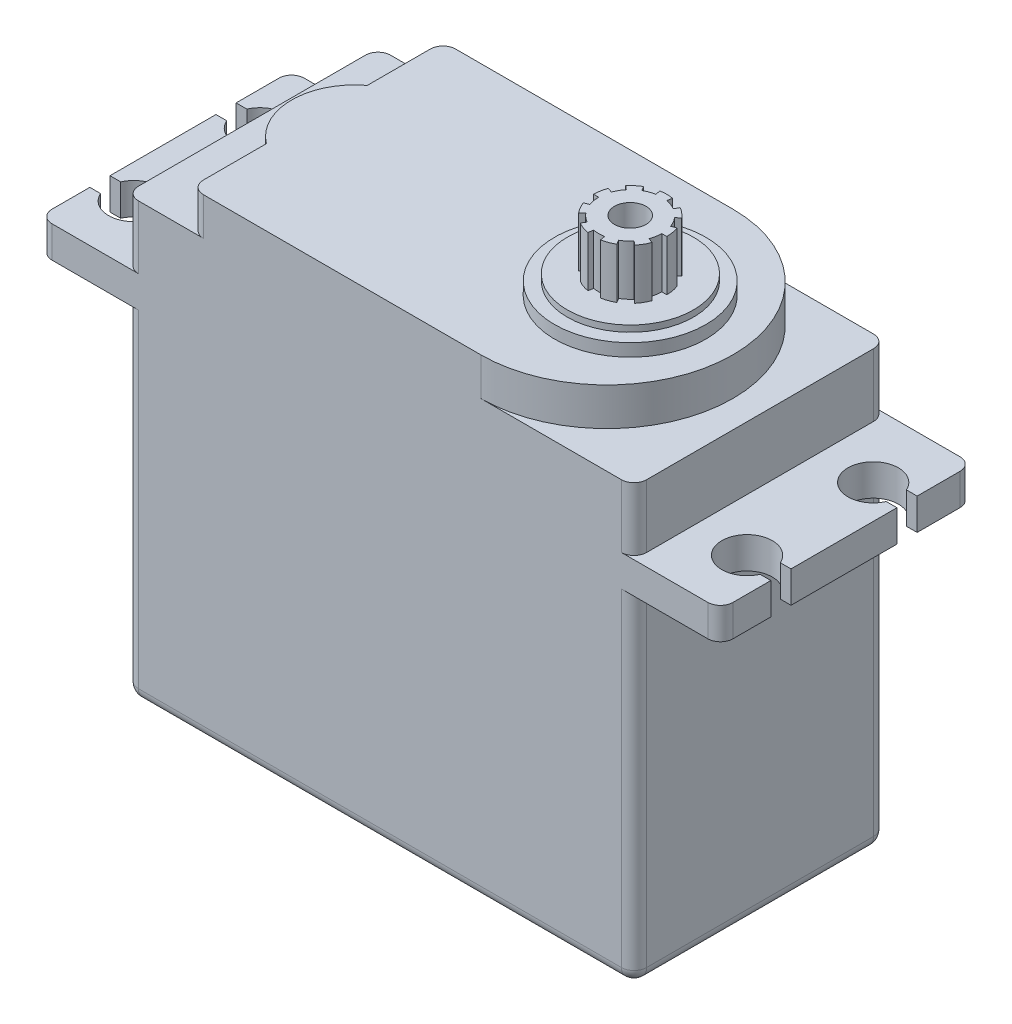
SolidWorks part; units mm, degrees
ref_plane "前视基准面" through (0, 0, 0) normal (0, 0, 1) x (1, 0, 0)
ref_plane "上视基准面" through (0, 0, 0) normal (0, 1, 0) x (1, 0, 0)
ref_plane "右视基准面" through (0, 0, 0) normal (1, 0, 0) x (0, 0, -1)
sketch "草图1" plane through (0, 0, 0) normal (0, 0, 1) x (1, 0, 0)
  line L0 (0, 0) -> (-50000, 0) construction
  line L1 (0, 0) -> (0, 50000) construction
  line L2 (20.15, 8) -> (27, 8)
  line L3 (-20.15, 18.5) -> (20.15, 18.5)
  line L4 (-20.15, 18.5) -> (-20.15, 10.5)
  line L5 (-20.15, -19) -> (20.15, -19)
  line L6 (20.15, 18.5) -> (20.15, 10.5)
  line L7 (-27, 10.5) -> (-20.15, 10.5)
  line L8 (-27, 10.5) -> (-27, 8)
  line L9 (-27, 8) -> (-20.15, 8)
  line L10 (27, 10.5) -> (27, 8)
  line L11 (20.15, 10.5) -> (27, 10.5)
  line L12 (20.15, 8) -> (20.15, -19)
  line L13 (-20.15, 8) -> (-20.15, -19)
  dimension "D1" = 8
  dimension "D2" = 6.85
  dimension "D3" = 2.5
  dimension "D4" = 40.3
  dimension "D5" = 27
  dimension "D6" = 54
  dimension "D7" = 20.15
extrude "凸台-拉伸1" add sketch "草图1" along normal blind 20
fillet "圆角1" radius 1 18 edges at (-20.15, 14.5, 20) (20.15, 14.5, 20) (20.15, 18.5, 10) (-20.15, 18.5, 10) (20.15, 14.5, 0) (-20.15, 14.5, 0) (-20.15, -19, 10) (0, -19, 20) (20.15, -19, 10) (0, -19, 0) (-20.15, -5.5, 0) (20.15, -5.5, 0) (20.15, -5.5, 20) (-20.15, -5.5, 20) (27, 9.25, 0) (27, 9.25, 20) (-27, 9.25, 0) (-27, 9.25, 20)
sketch "草图2" plane through (0, 10.5, 0) normal (0, 1, 0) x (1, 0, 0)
  line L0 (-0.1717, -10.2) -> (49999.8283, -10.2) construction
  line L1 (0, 0) -> (0, -50000) construction
  line L2 (-26.148, -4.4) -> (-29.2227, -4.4)
  line L3 (-24.315, -5.2) -> (-30.8838, -5.2) construction
  line L4 (-24, -15) -> (-30.5688, -15) construction
  line L5 (-29.2227, -4.4) -> (-29.2227, -6)
  line L6 (-26.148, -6) -> (-29.2227, -6)
  line L7 (-26.148, -14.4) -> (-29.2227, -14.4)
  line L8 (-29.2227, -16) -> (-29.2227, -14.4)
  line L9 (-26.148, -16) -> (-29.2227, -16)
  line L10 (26.148, -16) -> (29.2227, -16)
  line L11 (29.2227, -16) -> (29.2227, -14.4)
  line L12 (26.148, -14.4) -> (29.2227, -14.4)
  line L13 (29.2227, -4.4) -> (29.2227, -6)
  line L14 (26.148, -6) -> (29.2227, -6)
  line L15 (26.148, -4.4) -> (29.2227, -4.4)
  arc A0 (-26.148, -14.4) -> (-26.148, -16) centre (-24.315, -15.2) cw
  arc A1 (26.148, -14.4) -> (26.148, -16) centre (24.315, -15.2) ccw
  arc A2 (-26.148, -6) -> (-26.148, -4.4) centre (-24.315, -5.2) ccw
  arc A3 (26.148, -6) -> (26.148, -4.4) centre (24.315, -5.2) cw
  point P21 (-29.2227, -5.2)
  dimension "D2" = 10
  dimension "D1" = 48.63
  dimension "D3" = 2
extrude "切除-拉伸1" cut sketch "草图2" against normal blind 20
sketch "草图3" plane through (0, 18.5, 0) normal (0, 1, 0) x (1, 0, 0)
  line L0 (-40.2617, -10) -> (49959.7383, -10) construction
  line L1 (-14, 0) -> (8, 0)
  line L2 (-15, -1) -> (-15, -6)
  line L3 (-14, -20) -> (8, -20)
  line L4 (-15, -14) -> (-15, -19)
  line L5 (0, 0) -> (0, 50000) construction
  line L7 (-26.8677, 6.7729) -> (25, 6.7729)
  line L8 (-26.8677, 6.7729) -> (-26.8677, -28.4888)
  line L9 (-26.8677, -28.4888) -> (25, -28.4888)
  line L10 (25, 6.7729) -> (25, -28.4888)
  arc A0 (8, -20) -> (8, 0) centre (8, -10) ccw
  arc A1 (-15, -6) -> (-15, -14) centre (-12, -10) ccw
  arc A2 (-14, -20) -> (-15, -19) centre (-14, -19) cw
  arc A3 (-15, -1) -> (-14, 0) centre (-14, -1) cw
  dimension "D2" = 1
  dimension "D1" = 25
extrude "切除-拉伸2" cut sketch "草图3" against normal blind 3
sketch "草图4" plane through (0, 18.5, 0) normal (0, 1, 0) x (1, 0, 0)
  line L0 (27, -14.4) -> (27, -6) construction
  circle A0 centre (9.85, -10) radius 6
  dimension "D1" = 17.15
extrude "凸台-拉伸2" add sketch "草图4" along normal blind 1
sketch "草图5" plane through (0, 19.5, 0) normal (0, 1, 0) x (1, 0, 0)
  line L0 (27, -14.4) -> (27, -6) construction
  circle A0 centre (9.8513, -9.9876) radius 5
  point P2 (27, -10.2)
  dimension "D1" = 17.15
extrude "凸台-拉伸3" add sketch "草图5" along normal blind 0.5
sketch "草图6" plane through (0, 20, 0) normal (0, 1, 0) x (1, 0, 0)
  line L1 (10.2841, -7.538) -> (10.3536, -7.1441)
  line L3 (11.3, -7.4885) -> (11.1, -7.8349)
  line L5 (12.0715, -8.1359) -> (11.7651, -8.393)
  line L7 (12.5751, -9.0081) -> (12.1992, -9.1449)
  line L8 (6.95, -10) -> (7.35, -10)
  line L10 (7.5008, -9.1449) -> (7.1249, -9.0081)
  line L13 (8.6, -7.8349) -> (8.4, -7.4885)
  line L14 (7.9349, -8.393) -> (7.6285, -8.1359)
  line L15 (9.4159, -7.538) -> (9.3464, -7.1441)
  line L16 (9.4159, -12.462) -> (9.3464, -12.8559)
  line L19 (8.4, -12.5115) -> (8.6, -12.1651)
  line L20 (27, -14.4) -> (27, -6) construction
  line L21 (7.6285, -11.8641) -> (7.9349, -11.607)
  line L23 (7.1249, -10.9919) -> (7.5008, -10.8551)
  line L25 (12.1992, -10.8551) -> (12.5751, -10.9919)
  line L28 (11.1, -12.1651) -> (11.3, -12.5115)
  line L29 (10.2841, -12.462) -> (10.3536, -12.8559)
  line L30 (11.7651, -11.607) -> (12.0715, -11.8641)
  line L31 (12.35, -10) -> (12.75, -10)
  arc A0 (7.1249, -10.9919) -> (7.6285, -11.8641) centre (9.85, -10) ccw
  arc A1 (7.35, -10) -> (7.5008, -10.8551) centre (9.85, -10) ccw
  arc A2 (7.1249, -9.0081) -> (6.95, -10) centre (9.85, -10) ccw
  arc A3 (8.4, -7.4885) -> (7.6285, -8.1359) centre (9.85, -10) ccw
  arc A4 (10.3536, -7.1441) -> (9.3464, -7.1441) centre (9.85, -10) ccw
  arc A5 (12.0715, -8.1359) -> (11.3, -7.4885) centre (9.85, -10) ccw
  arc A6 (12.75, -10) -> (12.5751, -9.0081) centre (9.85, -10) ccw
  arc A7 (12.0715, -11.8641) -> (12.5751, -10.9919) centre (9.85, -10) ccw
  arc A8 (10.3536, -12.8559) -> (11.3, -12.5115) centre (9.85, -10) ccw
  arc A9 (8.4, -12.5115) -> (9.3464, -12.8559) centre (9.85, -10) ccw
  arc A10 (7.9349, -8.393) -> (7.5008, -9.1449) centre (9.85, -10) ccw
  arc A11 (9.4159, -7.538) -> (8.6, -7.8349) centre (9.85, -10) ccw
  arc A12 (11.1, -7.8349) -> (10.2841, -7.538) centre (9.85, -10) ccw
  arc A13 (12.1992, -9.1449) -> (11.7651, -8.393) centre (9.85, -10) ccw
  arc A14 (12.1992, -10.8551) -> (12.35, -10) centre (9.85, -10) ccw
  arc A15 (11.1, -12.1651) -> (11.7651, -11.607) centre (9.85, -10) ccw
  arc A16 (9.4159, -12.462) -> (10.2841, -12.462) centre (9.85, -10) ccw
  arc A17 (7.9349, -11.607) -> (8.6, -12.1651) centre (9.85, -10) ccw
  circle A18 centre (9.85, -10) radius 1
  dimension "D1" = 17.15
extrude "凸台-拉伸4" add sketch "草图6" along normal blind 4
hole_wizard "M3 螺纹孔1" positions "3D草图2" profile "草图8" tap size "M3" standard "GB"
sketch3d "3D草图2"
  line L0 (9.85, 24, 10) -> (9.85, 20, 10) construction
  point P0 (9.85, 24, 10)
sketch "草图8" plane through (9.85, 24, 10) normal (1, 0, 0) x (0, 0, 1)
  line L0 (0, 0) -> (0, 8.2511)
  line L1 (0, 8.2511) -> (1.25, 7.5)
  line L2 (1.25, 7.5) -> (1.25, 0)
  line L5 (1.25, 0) -> (0, 0)
  line L10 (0, 8.2511) -> (-1.25, 7.5) construction
  line L11 (0, -6.35) -> (0, 107.95) construction
  dimension "螺纹孔钻头直径" = 2.5
  dimension "螺纹孔钻头深度" = 7.5
  dimension "导头角度" = 118
cosmetic thread "孔螺蚊线1" parameters "D1"=6, "D2"=3
sketch "草图11" plane through (0, -19, 0) normal (0, -1, 0) x (1, 0, 0)
sketch "草图13" plane through (0, -19, 0) normal (0, -1, 0) x (1, 0, 0)
  line L0 (-26, 20) -> (27.9876, 20) construction
  line L1 (27, 12.7131) -> (27, 23.1574) construction
  line L3 (22.575, 0) -> (10.8115, 0) construction
  line L6 (-27, 1.9016) -> (-27, 21.4847) construction
  line L8 (-20.15, 16.5481) -> (-20.15, 10) construction
  line L10 (20.15, 11.6115) -> (20.15, 23.7286) construction
  line L12 (-24.315, 15.2) -> (-24.315, 20) construction
  line L13 (-24.315, 15.2) -> (-27, 15.2) construction
  line L14 (-26.148, 14.4) -> (-27, 14.4) construction
  circle A5 centre (24.315, 5.2) radius 2
  circle A6 centre (24.315, 15.2) radius 2
  dimension "D2" = 4.165
  dimension "D7" = 10
  dimension "D1" = 1.6
  dimension "D3" = 4.8
  dimension "D4" = 54
  dimension "D5" = 20
  dimension "D6" = 40.3
